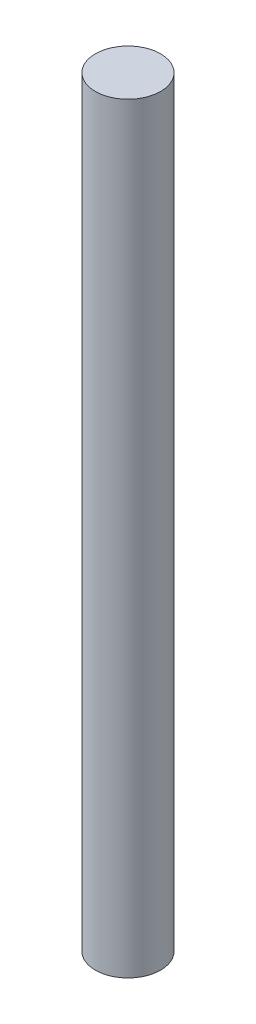
SolidWorks part; units mm, degrees
ref_plane "Front Plane" through (0, 0, 0) normal (0, 0, 1) x (1, 0, 0)
ref_plane "Top Plane" through (0, 0, 0) normal (0, 1, 0) x (1, 0, 0)
ref_plane "Right Plane" through (0, 0, 0) normal (1, 0, 0) x (0, 0, -1)
sketch "Sketch1" plane through (0, 0, 0) normal (0, 1, 0) x (1, 0, 0)
  circle A0 centre (0, 0) radius 1.5
  dimension "D1" = 3
extrude "Boss-Extrude1" add sketch "Sketch1" along normal blind 35
